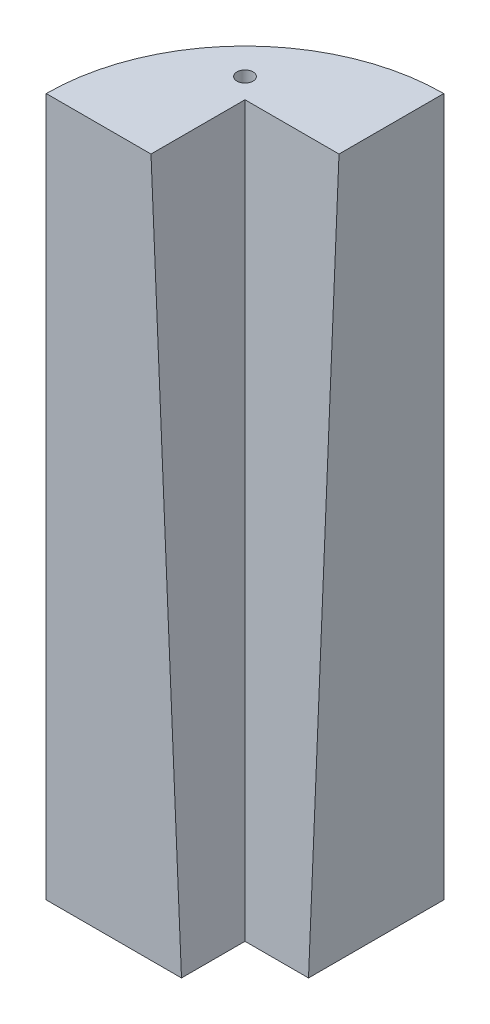
SolidWorks part; units mm, degrees
ref_plane "Front Plane" through (0, 0, 0) normal (0, 0, 1) x (1, 0, 0)
ref_plane "Top Plane" through (0, 0, 0) normal (0, 1, 0) x (1, 0, 0)
ref_plane "Right Plane" through (0, 0, 0) normal (1, 0, 0) x (0, 0, -1)
sketch "Sketch1" plane through (0, 0, 0) normal (0, 1, 0) x (1, 0, 0)
  circle A0 centre (0, 0) radius 46.99
  dimension "D1" = 93.98
extrude "Boss-Extrude1" add sketch "Sketch1" along normal blind 330.2
sketch "Sketch2" plane through (0, 330.2, 0) normal (0, 1, 0) x (1, 0, 0)
  line L0 (-46.99, 0) -> (46.99, 0) construction
  line L1 (0, 46.99) -> (0, -46.99) construction
  line L3 (-22.225, 22.225) -> (22.225, 22.225)
  line L4 (-22.225, 22.225) -> (-22.225, -22.225)
  line L5 (-22.225, -22.225) -> (22.225, -22.225)
  line L6 (22.225, 22.225) -> (22.225, -22.225)
  circle A0 centre (0, 0) radius 46.99 construction
  dimension "D1" = 44.45
  dimension "D2" = 44.45
  dimension "D3" = 22.225
  dimension "D4" = 22.225
extrude "Cut-Extrude1" cut sketch "Sketch2" against normal blind 330.2 draft 2.5
sketch "Sketch3" plane through (0, 330.2, 0) normal (0, 1, 0) x (1, 0, 0)
  line L2 (0, 12.7) -> (0, 46.99)
  line L3 (-12.7, 0) -> (-46.99, 0)
  line L6 (0, 12.7) -> (0, 0)
  line L7 (0, 0) -> (-12.7, 0)
  line L8 (-22.225, 22.225) -> (-22.225, -22.225) construction
  line L9 (22.225, 22.225) -> (-22.225, 22.225) construction
  arc A0 (-46.99, 0) -> (0, 46.99) centre (0, 0) ccw
  circle A1 centre (0, 0) radius 46.99 construction
  circle A3 centre (-26.9875, 26.9875) radius 1.905
  dimension "D1" = 3.81
  dimension "D2" = 4.7625
  dimension "D3" = 4.7625
extrude "Cut-Extrude2" cut sketch "Sketch3" against normal blind 330.2
sketch "Sketch5" plane through (0, 0, 0) normal (0, -1, 0) x (1, 0, 0)
  line L0 (-46.99, 0) -> (0, 0)
  line L1 (0, 0) -> (0, -46.99)
  arc A0 (-46.99, 0) -> (0, -46.99) centre (0, 0) ccw
extrude "Cut-Extrude3" cut sketch "Sketch5" against normal blind 165.1
sketch "Sketch6" plane through (0, 165.1, 0) normal (0, -1, 0) x (1, 0, 0)
  circle A0 centre (-31.75, -12.7) radius 4.7625
  circle A1 centre (-12.7, -31.75) radius 4.7625
  dimension "D1" = 9.525
  dimension "D2" = 9.525
  dimension "D3" = 31.75
  dimension "D4" = 12.7
  dimension "D5" = 12.7
  dimension "D6" = 31.75
extrude "Boss-Extrude3" add sketch "Sketch6" along normal blind 4.7625 draft 45
